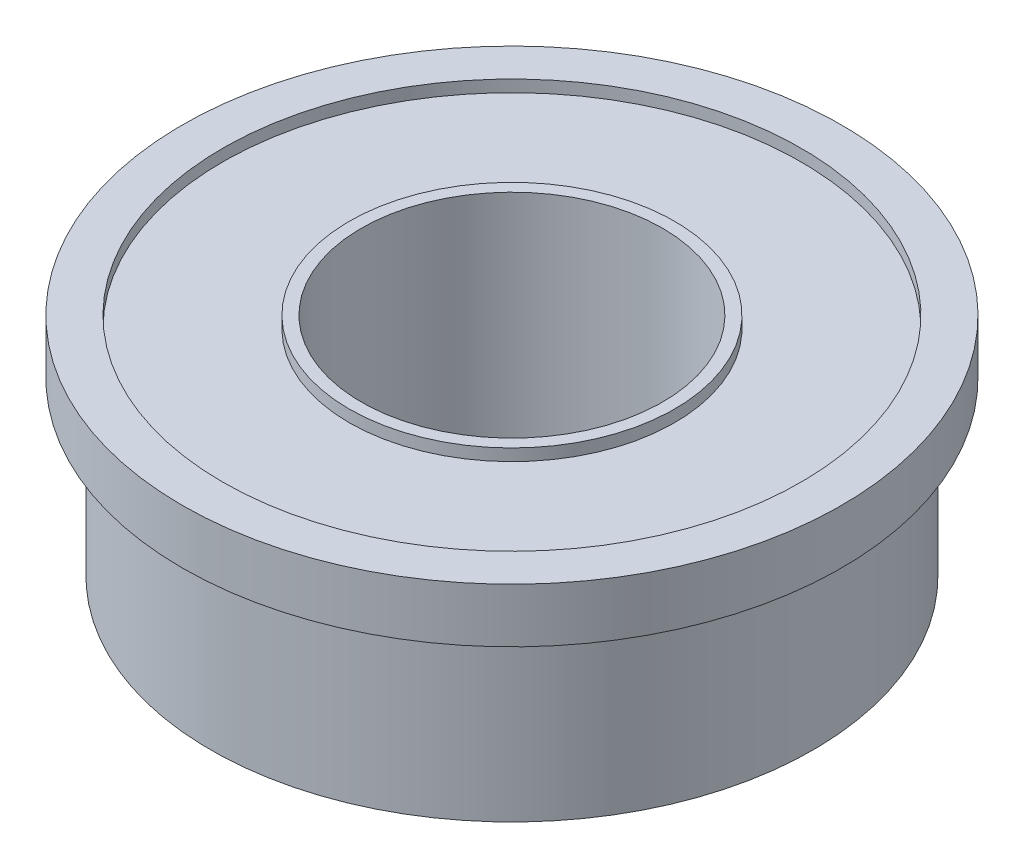
SolidWorks part; units mm, degrees
ref_plane "Front Plane" through (0, 0, 0) normal (0, 0, 1) x (1, 0, 0)
ref_plane "Top Plane" through (0, 0, 0) normal (0, 1, 0) x (1, 0, 0)
ref_plane "Right Plane" through (0, 0, 0) normal (1, 0, 0) x (0, 0, -1)
sketch "Sketch1" plane through (0, 0, 0) normal (0, 1, 0) x (1, 0, 0)
  circle A0 centre (0, 0) radius 3.175
  circle A1 centre (0, 0) radius 6.35
  dimension "D1" = 12.7
  dimension "D2" = 6.35
extrude "Boss-Extrude1" add sketch "Sketch1" along normal blind 4.7625
sketch "Sketch2" plane through (0, 4.7625, 0) normal (0, 1, 0) x (1, 0, 0)
  circle A0 centre (0, 0) radius 3.429
  circle A1 centre (0, 0) radius 6.096
  dimension "D1" = 6.858
  dimension "D2" = 12.192
extrude "Cut-Extrude1" cut sketch "Sketch2" against normal blind 0.25
ref_plane "Plane1" through (0, 2.3813, 0) normal (0, 1, 0) x (1, 0, 0)
mirror "Mirror1" about plane through (0, 2.3813, 0) normal (0, 1, 0) of "Cut-Extrude1"
sketch "Sketch3" plane through (0, 4.7625, 0) normal (0, 1, 0) x (1, 0, 0)
  circle A0 centre (0, 0) radius 6.9469
  circle A1 centre (0, 0) radius 6.35 construction
  circle A2 centre (0, 0) radius 6.35
  dimension "D1" = 13.8938
extrude "Boss-Extrude2" add sketch "Sketch3" against normal blind 1.143
